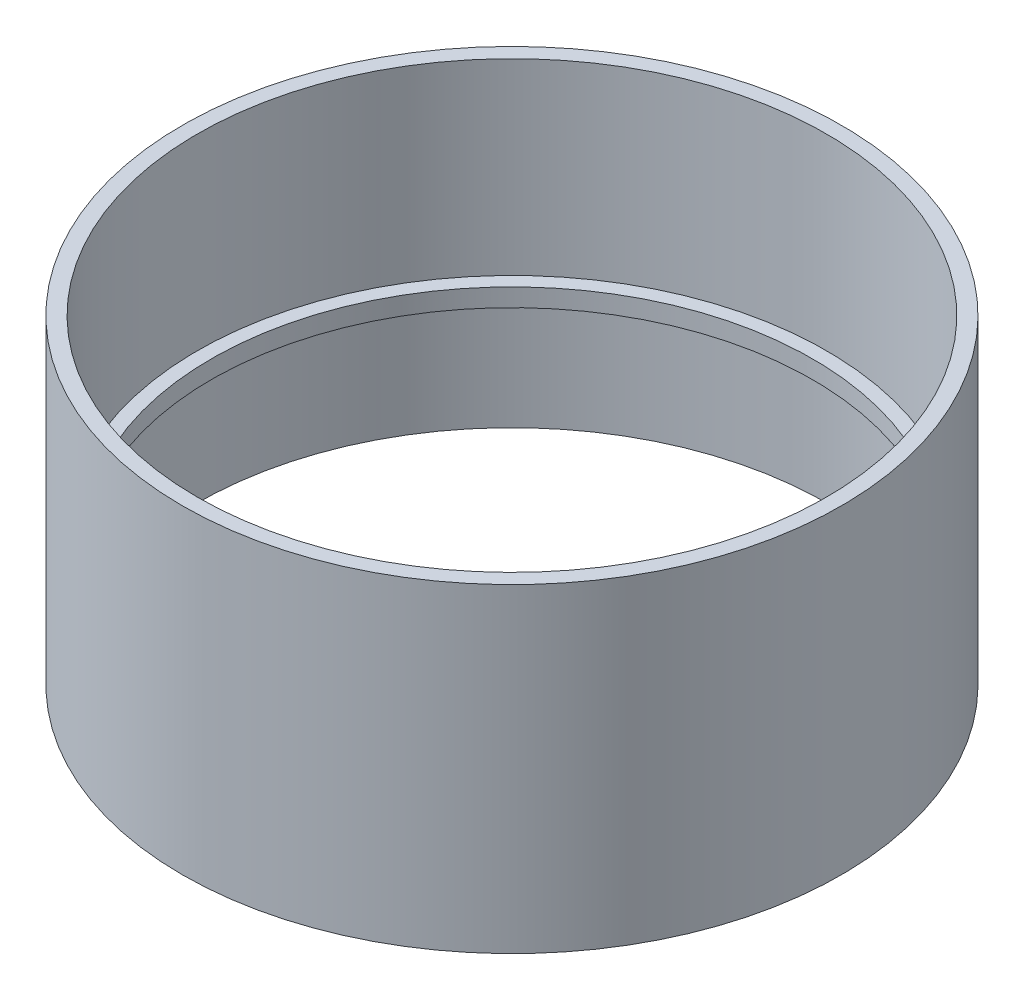
SolidWorks part; units mm, degrees
material "PVC Rígido"
ref_plane "Alzado" through (0, 0, 0) normal (0, 0, 1) x (1, 0, 0)
ref_plane "Planta" through (0, 0, 0) normal (0, 1, 0) x (1, 0, 0)
ref_plane "Vista lateral" through (0, 0, 0) normal (1, 0, 0) x (0, 0, -1)
sketch "Croquis2" plane through (0, 0, 0) normal (0, 1, 0) x (1, 0, 0)
  circle A0 centre (0, 0) radius 80.01
  circle A1 centre (0, 0) radius 83.82
  dimension "D1" = 160.02
  dimension "D2" = 3.81
extrude "Saliente-Extruir1" add sketch "Croquis2" against normal blind 81.28
ref_plane "Plano1" through (0, -47.752, 0) normal (0, 1, 0) x (1, 0, 0)
sketch "Croquis4" plane through (0, -47.752, 0) normal (0, 1, 0) x (1, 0, 0)
  circle A0 centre (0, 0) radius 80.01 construction
  circle A1 centre (0, 0) radius 80.01
  circle A2 centre (0, 0) radius 76.454
  dimension "D1" = 3.556
extrude "Saliente-Extruir2" add sketch "Croquis4" against normal blind 4.572
